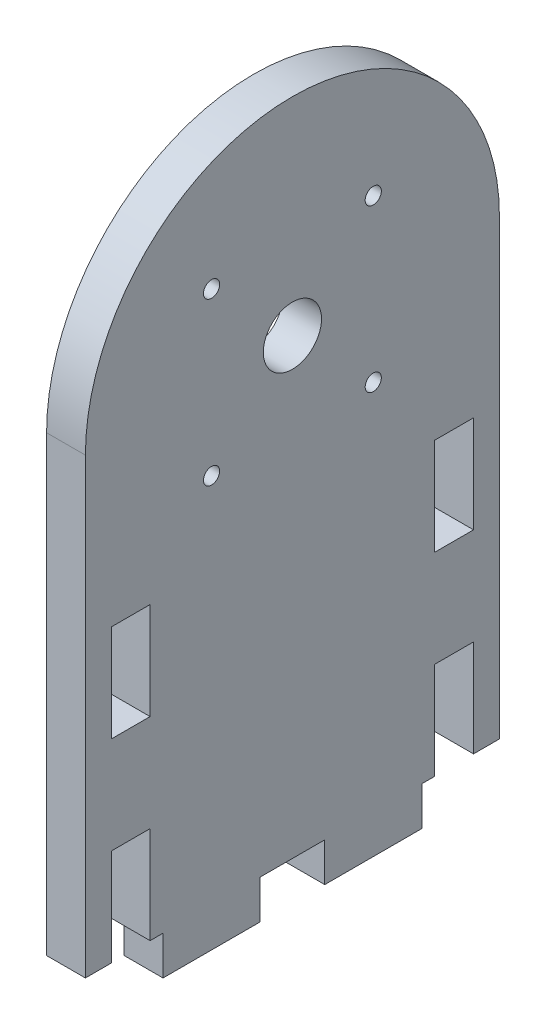
SolidWorks part; units mm, degrees
material "6061-T6 (SS)"
ref_plane "Alzado" through (0, 0, 0) normal (0, 0, 1) x (1, 0, 0)
ref_plane "Planta" through (0, 0, 0) normal (0, 1, 0) x (1, 0, 0)
ref_plane "Vista lateral" through (0, 0, 0) normal (1, 0, 0) x (0, 0, -1)
sketch "Croquis1" plane through (0, 0, 0) normal (1, 0, 0) x (0, 0, -1)
  line L0 (-32, -35) -> (-32, 35)
  line L1 (32, 35) -> (32, -35)
  line L2 (32, -35) -> (-32, -35)
  line L3 (0, -35) -> (0, 35) construction
  arc A0 (-32, 35) -> (32, 35) centre (0, 35) cw
  circle A1 centre (0, 35) radius 4.5
  point P6 (0, 0)
  dimension "D3" = 9
  dimension "D1" = 70
  dimension "D2" = 64
extrude "Saliente-Extruir1" add sketch "Croquis1" along normal mid plane 6
hole_wizard "Taladro roscado M3x0.51" positions "Croquis4" profile "Croquis5" tap size "M3x0.5" standard "Ansi Metric" end condition up to next
sketch "Croquis4" plane through (3, 0, 0) normal (1, 0, 0) x (0, 0, -1)
  point P0 (12.5, 47.5)
  point P2 (12.5, 22.5)
  point P4 (-12.5, 22.5)
  point P6 (-12.5, 47.5)
sketch "Croquis5" plane through (3, 47.5, -12.5) normal (0, 1, 0) x (0, 0, -1)
  line L0 (0, 0) -> (0, 6)
  line L1 (0, 6) -> (1.25, 6)
  line L2 (1.25, 6) -> (1.25, 0)
  line L5 (1.25, 0) -> (0, 0)
  line L11 (0, -6.35) -> (0, 107.95) construction
  dimension "Diámetro de perforador para roscar hasta el siguiente" = 2.5
  dimension "Profundidad de perforador para roscar hasta el siguiente" = 6
cosmetic thread "Rosca de taladro1" parameters "D2"=3
cosmetic thread "Rosca de taladro2" parameters "D2"=3
cosmetic thread "Rosca de taladro3" parameters "D2"=3
cosmetic thread "Rosca de taladro4" parameters "D2"=3
sketch "Croquis6" plane through (3, 0, 0) normal (1, 0, 0) x (0, 0, -1)
  line L0 (0, 0) -> (0, -35) construction
  line L1 (-28, 10) -> (-22, 10)
  line L2 (-28, 10) -> (-28, -5)
  line L3 (-28, -5) -> (-22, -5)
  line L4 (-22, 10) -> (-22, -5)
  line L5 (-28, -20) -> (-22, -20)
  line L6 (-28, -20) -> (-28, -35)
  line L7 (-28, -35) -> (-22, -35)
  line L8 (-22, -20) -> (-22, -35)
  line L9 (-32, -35) -> (32, -35) construction
  line L10 (28, -35) -> (22, -35)
  line L11 (22, -20) -> (22, -35)
  line L12 (28, -20) -> (22, -20)
  line L13 (28, -20) -> (28, -35)
  line L14 (28, -5) -> (22, -5)
  line L15 (22, 10) -> (22, -5)
  line L16 (28, 10) -> (22, 10)
  line L17 (28, 10) -> (28, -5)
  dimension "D1" = 15
  dimension "D2" = 15
  dimension "D3" = 22
  dimension "D4" = 6
extrude "Cortar-Extruir1" cut sketch "Croquis6" against normal through all
sketch "Croquis7" plane through (3, 0, 0) normal (1, 0, 0) x (0, 0, -1)
  line L0 (-22, -35) -> (22, -35) construction
  line L1 (-20, -35) -> (-5, -35)
  line L2 (-20, -35) -> (-20, -41)
  line L3 (-20, -41) -> (-5, -41)
  line L4 (-5, -35) -> (-5, -41)
  line L5 (-5, -38) -> (5, -38) construction
  line L6 (5, -35) -> (20, -35)
  line L7 (5, -35) -> (5, -41)
  line L8 (5, -41) -> (20, -41)
  line L9 (20, -35) -> (20, -41)
  point P10 (0, -38)
  dimension "D1" = 15
  dimension "D2" = 6
  dimension "D3" = 10
extrude "Saliente-Extruir3" add sketch "Croquis7" against normal through all
